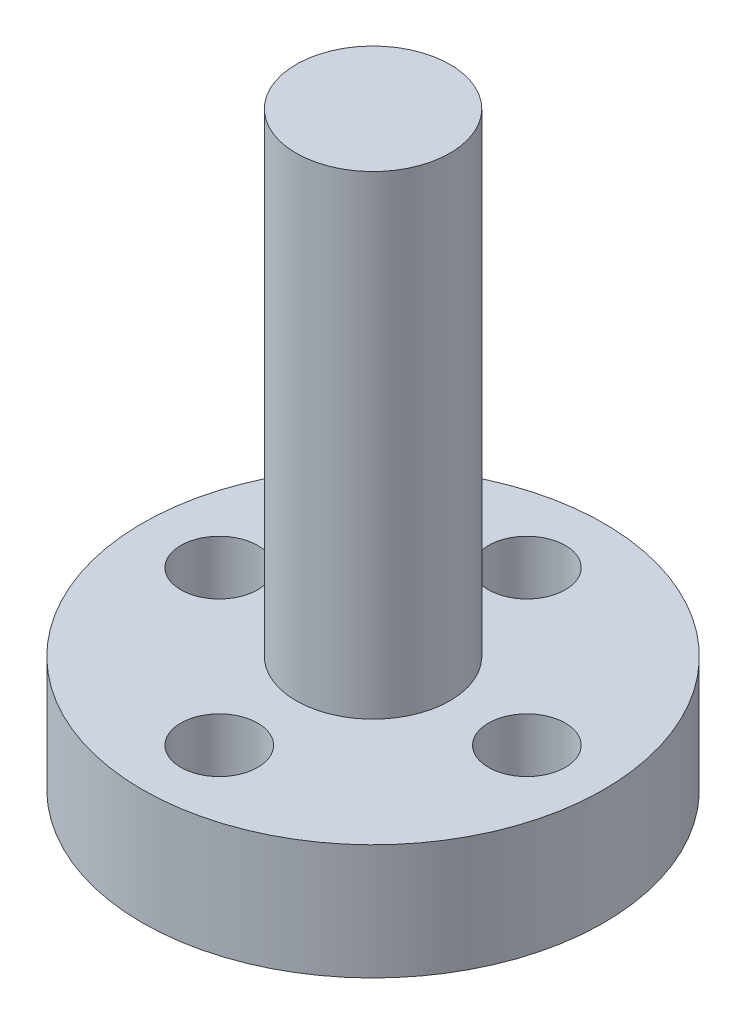
SolidWorks part; units mm, degrees
ref_plane "前视基准面" through (0, 0, 0) normal (0, 0, 1) x (1, 0, 0)
ref_plane "上视基准面" through (0, 0, 0) normal (0, 1, 0) x (1, 0, 0)
ref_plane "右视基准面" through (0, 0, 0) normal (1, 0, 0) x (0, 0, -1)
sketch "草图1" plane through (0, 0, 0) normal (0, 1, 0) x (1, 0, 0)
  circle A0 centre (0, 0) radius 9
  dimension "D1" = 18
extrude "凸台-拉伸1" add sketch "草图1" along normal blind 4.5
sketch "草图2" plane through (0, 0, 0) normal (0, -1, 0) x (1, 0, 0)
  circle A0 centre (0, 0) radius 2
  dimension "D1" = 4
extrude "切除-拉伸1" cut sketch "草图2" against normal blind 2
sketch "草图3" plane through (0, 0, 0) normal (0, -1, 0) x (1, 0, 0)
  circle A0 centre (0, 0) radius 6 construction
  circle A1 centre (0, 6) radius 1.5
  circle A2 centre (0, 0) radius 6 construction
  circle A3 centre (6, 0) radius 1.5
  circle A4 centre (0, 0) radius 6 construction
  circle A5 centre (0, -6) radius 1.5
  circle A6 centre (0, 0) radius 6 construction
  circle A7 centre (-6, 0) radius 1.5
  point P17 (0, 0)
  dimension "D1" = 12
  dimension "D2" = 3
  dimension "D3" = 4
extrude "切除-拉伸2" cut sketch "草图3" against normal through all
sketch "草图4" plane through (0, 4.5, 0) normal (0, 1, 0) x (1, 0, 0)
  circle A0 centre (0, 0) radius 3
  dimension "D1" = 6
extrude "凸台-拉伸2" add sketch "草图4" along normal blind 18.5
cosmetic thread "装饰螺纹线1" parameters "D1"=13.5, "D2"=4.917
